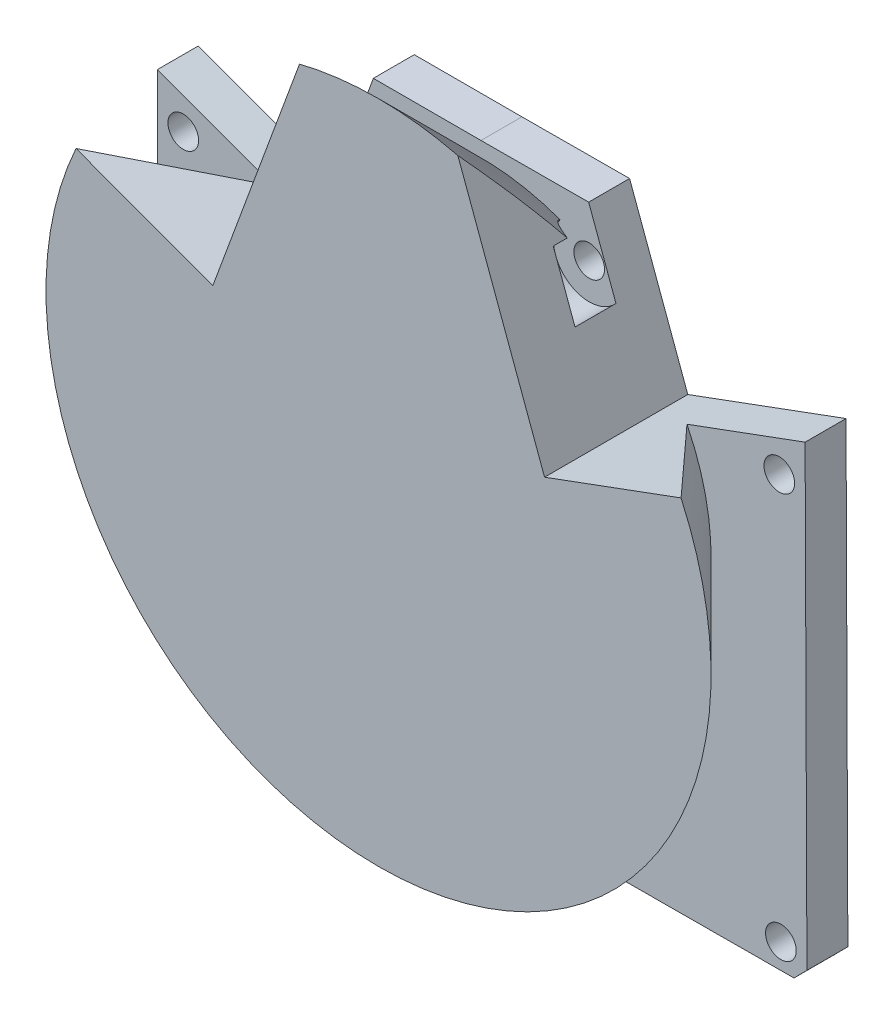
SolidWorks part; units mm, degrees
ref_plane "Front" through (0, 0, 0) normal (0, 0, 1) x (1, 0, 0)
ref_plane "Top" through (0, 0, 0) normal (0, 1, 0) x (1, 0, 0)
ref_plane "Right" through (0, 0, 0) normal (1, 0, 0) x (0, 0, -1)
sketch "20" plane through (0, 0, 0) normal (0, 0, 1) x (1, 0, 0)
  line L0 (1.27, 0) -> (62.23, 0)
  line L1 (63.5, 1.27) -> (63.5, 62.23)
  line L2 (62.23, 63.5) -> (58.039, 63.5)
  line L3 (37.846, 63.5) -> (25.4, 63.5)
  line L4 (5.207, 63.5) -> (1.27, 63.5)
  line L5 (0, 62.23) -> (0, 1.27)
  line L6 (5.969, 61.214) -> (20.32, 56.007)
  line L7 (20.32, 56.007) -> (25.4, 63.5)
  line L8 (5.969, 61.214) -> (5.207, 63.5)
  line L9 (57.277, 61.214) -> (42.926, 56.007)
  line L10 (42.926, 56.007) -> (37.846, 63.5)
  line L11 (57.277, 61.214) -> (58.039, 63.5)
  arc A0 (0, 1.27) -> (1.27, 0) centre (1.27, 1.27) ccw
  arc A1 (62.23, 0) -> (63.5, 1.27) centre (62.23, 1.27) ccw
  arc A2 (63.5, 62.23) -> (62.23, 63.5) centre (62.23, 62.23) ccw
  arc A3 (1.27, 63.5) -> (0, 62.23) centre (1.27, 62.23) ccw
  circle A4 centre (2.54, 2.54) radius 1.4986
  circle A5 centre (60.96, 20.32) radius 1.4986
  circle A6 centre (2.54, 41.91) radius 1.4986
  circle A7 centre (60.96, 41.91) radius 1.4986
  circle A8 centre (21.082, 50.8) radius 1.4986
  circle A9 centre (42.418, 50.8) radius 1.4986
  circle A10 centre (54.61, 3.81) radius 0.7
  circle A11 centre (54.61, 13.97) radius 0.7
  circle A12 centre (46.6997, 51.3854) radius 1.6256
  circle A13 centre (57.4403, 55.2946) radius 1.6256
  circle A14 centre (5.8057, 55.2946) radius 1.6256
  circle A15 centre (16.5463, 51.3854) radius 1.6256
sketch "22" plane through (0, 0, 0) normal (0, 0, 1) x (1, 0, 0)
  line L1 (48.6973, 40.5991) -> (62.8434, 45.7478)
  line L2 (58.121, 61.4079) -> (42.2487, 55.6309)
  line L3 (56.4815, 63.2271) -> (42.3353, 58.0783)
  line L4 (42.3353, 58.0783) -> (48.6973, 40.5991)
  line L5 (62.8434, 45.7478) -> (56.4815, 63.2271)
  line L6 (0.4026, 45.7478) -> (14.5488, 40.5991)
  line L7 (20.9973, 55.6309) -> (5.125, 61.4079)
  line L8 (20.9107, 58.0783) -> (6.7645, 63.2271)
  line L9 (6.7645, 63.2271) -> (0.4026, 45.7478)
  line L10 (14.5488, 40.5991) -> (20.9107, 58.0783)
  arc A2 (62.8608, 45.7001) -> (62.826, 45.7956) centre (62.8434, 45.7478) ccw
  arc A3 (48.6799, 40.6468) -> (48.7146, 40.5513) centre (48.6972, 40.599) ccw
  arc A4 (42.2313, 55.6786) -> (42.2661, 55.5831) centre (42.2487, 55.6309) ccw
  arc A5 (58.1384, 61.3602) -> (58.1037, 61.4557) centre (58.1211, 61.4079) ccw
  arc A6 (42.318, 58.126) -> (42.3527, 58.0306) centre (42.3353, 58.0783) ccw
  arc A7 (56.4988, 63.1793) -> (56.4641, 63.2748) centre (56.4815, 63.2271) ccw
  arc A8 (48.6495, 40.5817) -> (48.745, 40.6165) centre (48.6972, 40.5991) ccw
  arc A9 (42.3831, 58.0957) -> (42.2876, 58.0609) centre (42.3353, 58.0783) ccw
  arc A10 (56.5292, 63.2444) -> (56.4337, 63.2097) centre (56.4815, 63.2271) ccw
  arc A11 (62.7956, 45.7305) -> (62.8911, 45.7652) centre (62.8434, 45.7478) ccw
  arc A12 (14.5314, 40.5513) -> (14.5661, 40.6468) centre (14.5487, 40.599) ccw
  arc A13 (0.42, 45.7956) -> (0.3852, 45.7001) centre (0.4026, 45.7478) ccw
  arc A14 (5.1423, 61.4557) -> (5.1076, 61.3602) centre (5.1249, 61.4079) ccw
  arc A15 (20.9799, 55.5831) -> (21.0147, 55.6786) centre (20.9973, 55.6309) ccw
  arc A16 (6.7819, 63.2748) -> (6.7472, 63.1793) centre (6.7645, 63.2271) ccw
  arc A17 (20.8933, 58.0306) -> (20.928, 58.126) centre (20.9107, 58.0783) ccw
  arc A18 (0.3549, 45.7652) -> (0.4504, 45.7305) centre (0.4027, 45.7478) ccw
  arc A19 (6.8123, 63.2097) -> (6.7168, 63.2444) centre (6.7645, 63.2271) ccw
  arc A20 (20.9584, 58.0609) -> (20.8629, 58.0957) centre (20.9107, 58.0783) ccw
  arc A21 (14.501, 40.6165) -> (14.5965, 40.5817) centre (14.5488, 40.5991) ccw
sketch "Sketch9" plane through (0, 0, 0) normal (0, 0, 1) x (1, 0, 0)
  line L0 (31.623, 63.5) -> (31.75, 0) construction
  line L1 (37.846, 63.5) -> (25.4, 63.5) construction
  line L2 (1.27, 0) -> (62.23, 0) construction
  line L3 (0, 45.8943) -> (15.4885, 40.2571)
  line L4 (0.4026, 45.7478) -> (14.5488, 40.5991) construction
  line L5 (14.5488, 40.5991) -> (20.9107, 58.0783) construction
  line L6 (60.96, 20.32) -> (2.4587, 20.32) construction
  line L7 (15.4885, 40.2571) -> (21.1158, 55.7183)
  line L8 (21.1158, 55.7183) -> (31.6386, 55.7183)
  line L9 (5.969, 61.214) -> (20.32, 56.007) construction
  line L10 (0, 62.23) -> (0, 1.27) construction
  line L11 (0, 45.8943) -> (0, 1.27)
  line L12 (0, 1.27) -> (1.27, 0)
  line L13 (1.27, 0) -> (31.75, 0)
  line L14 (62.2298, 0.1219) -> (31.75, 0)
  line L15 (63.4947, 1.397) -> (62.2298, 0.1219)
  line L16 (63.3162, 46.021) -> (63.4947, 1.397)
  line L17 (63.3162, 46.021) -> (47.8503, 40.3218)
  line L18 (47.8503, 40.3218) -> (42.1612, 55.7604)
  line L19 (42.1612, 55.7604) -> (31.6386, 55.7183)
  line L20 (2.54, 2.54) -> (60.9498, 2.54) construction
  circle A0 centre (60.9498, 2.54) radius 1.4986
  circle A1 centre (21.082, 50.8) radius 1.4986
  circle A2 centre (2.54, 41.91) radius 1.4986
  circle A4 centre (2.54, 41.91) radius 1.4986 construction
  circle A5 centre (21.082, 50.8) radius 1.4986 construction
  circle A6 centre (2.54, 2.54) radius 1.4986 construction
  circle A7 centre (60.7921, 42.0265) radius 1.4986
  circle A8 centre (42.2147, 50.8423) radius 1.4986
  circle A10 centre (2.4587, 20.32) radius 1.4986
  circle A11 centre (60.96, 20.32) radius 1.4986 construction
  point P7 (31.6865, 31.75)
  point P41 (31.7449, 2.54)
  point P51 (31.7094, 20.32)
  point P57 (27.629, 2.54)
  point P58 (28.3405, 2.54)
  point P59 (31.7449, 2.54)
  dimension "D1" = 1
extrude "Boss-Extrude2" add sketch "Sketch9" along normal blind 4
sketch "Sketch10" plane through (0, 0, 4) normal (0, 0, 1) x (1, 0, 0)
  line L0 (31.623, 63.5) -> (31.623, 0) construction
  line L1 (1.27, 0) -> (31.75, 0) construction
  line L2 (37.846, 63.5) -> (25.4, 63.5) construction
  circle A0 centre (31.623, 31.75) radius 22.5
  dimension "D1" = 45
extrude "Boss-Extrude3" add sketch "Sketch10" along normal blind 10 draft 45 draft outward yes
sketch "Sketch11" plane through (0, 0, 4) normal (0, 0, 1) x (1, 0, 0)
  line L0 (63.3162, 46.021) -> (54.6719, 69.4789)
  line L1 (63.3162, 46.021) -> (47.8503, 40.3218)
  line L2 (47.8503, 40.3218) -> (42.1612, 55.7604)
  line L3 (54.6719, 69.4789) -> (39.2061, 63.7798)
  line L4 (39.2061, 63.7798) -> (42.1612, 55.7604)
  line L5 (31.6386, 55.7193) -> (31.6386, 73.7322) construction
  line L7 (42.1612, 55.7604) -> (31.6386, 55.7183) construction
  line L8 (31.6386, 55.7183) -> (21.1158, 55.7183) construction
  line L9 (-0.039, 46.021) -> (15.4268, 40.3218)
  line L10 (15.4268, 40.3218) -> (21.1159, 55.7604)
  line L11 (24.071, 63.7798) -> (21.1159, 55.7604)
  line L12 (-0.039, 46.021) -> (8.6052, 69.4789)
  line L13 (8.6052, 69.4789) -> (24.071, 63.7798)
  point P9 (31.6386, 55.7183)
  dimension "D1" = 25
extrude "Cut-Extrude1" cut sketch "Sketch11" along normal blind 10
sketch "Sketch12" plane through (0, 0, 4) normal (0, 0, 1) x (1, 0, 0)
  line L0 (31.6386, 55.7183) -> (31.6386, 78.9266) construction
  circle A1 centre (21.0624, 50.8423) radius 3.4986
  circle A2 centre (42.2147, 50.8423) radius 3.4986
  circle A3 centre (42.2147, 50.8423) radius 3.4986
  point P1 (31.6386, 55.7183)
  dimension "D1" = 2
extrude "Cut-Extrude2" cut sketch "Sketch12" along normal blind 4
